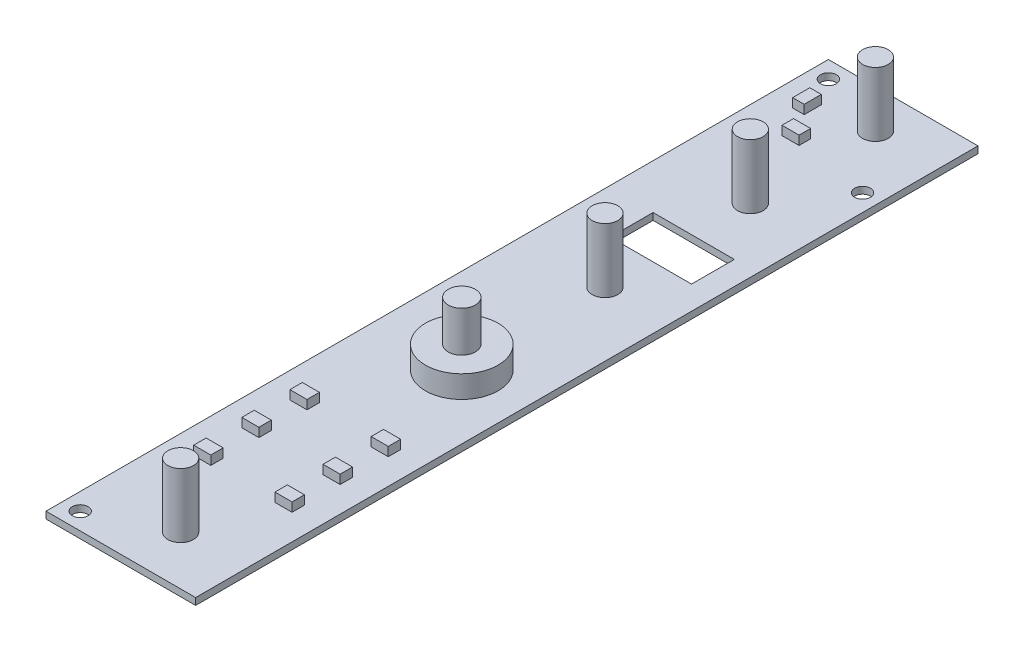
SolidWorks part; units mm, degrees
ref_plane "Front Plane" through (0, 0, 0) normal (0, 0, 1) x (1, 0, 0)
ref_plane "Top Plane" through (0, 0, 0) normal (0, 1, 0) x (1, 0, 0)
ref_plane "Right Plane" through (0, 0, 0) normal (1, 0, 0) x (0, 0, -1)
sketch "pcb" plane through (0, 0, 0) normal (0, 1, 0) x (1, 0, 0)
  line L1 (-17.5, 91.5) -> (17.5, 91.5)
  line L2 (-17.5, 91.5) -> (-17.5, -91.5)
  line L3 (-17.5, -91.5) -> (17.5, -91.5)
  line L4 (17.5, 91.5) -> (17.5, -91.5)
  line L5 (-17.5, 91.5) -> (17.5, -91.5) construction
  line L6 (-17.5, -91.5) -> (17.5, 91.5) construction
  point P0 (0, 0)
  dimension "D1" = 183
  dimension "D2" = 35
extrude "Boss-Extrude1" add sketch "pcb" along normal blind 1.6
sketch "Sketch3" plane through (0, 1.6, 0) normal (0, 1, 0) x (1, 0, 0)
  line L0 (17.5, 91.5) -> (-17.5, 91.5) construction
  line L1 (-17.5, 91.5) -> (-17.5, -91.5) construction
  circle A0 centre (2.5, 82.5) radius 3
  circle A1 centre (2.5, 53.25) radius 3
  circle A2 centre (2.5, 19.25) radius 3
  circle A3 centre (2.5, -80) radius 3
  dimension "D3" = 6
  dimension "D1" = 9
  dimension "D2" = 20
  dimension "D4" = 38.25
  dimension "D5" = 72.25
  dimension "D6" = 171.5
extrude "Boss-Extrude2" add sketch "Sketch3" along normal blind 15
sketch "Sketch4" plane through (0, 1.6, 0) normal (0, 1, 0) x (1, 0, 0)
  line L0 (17.5, 91.5) -> (-17.5, 91.5) construction
  line L1 (-17.5, 91.5) -> (-17.5, -91.5) construction
  circle A0 centre (2.5, -14.25) radius 8.5
  dimension "D3" = 17
  dimension "D1" = 105.75
  dimension "D2" = 20
extrude "Boss-Extrude3" add sketch "Sketch4" along normal blind 5.21
sketch "Sketch5" plane through (0, 6.81, 0) normal (0, 1, 0) x (1, 0, 0)
  circle A0 centre (2.5, -14.25) radius 3.175
  circle A1 centre (2.5, -14.25) radius 8.5 construction
  dimension "D1" = 6.35
extrude "Boss-Extrude4" add sketch "Sketch5" along normal blind 9.52
sketch "Sketch6" plane through (0, 1.6, 0) normal (0, 1, 0) x (1, 0, 0)
  line L0 (-17.5, 91.5) -> (-17.5, -91.5) construction
  line L1 (-11.5, -37.55) -> (-7.5, -37.55)
  line L2 (-11.5, -37.55) -> (-11.5, -40.45)
  line L3 (-11.5, -40.45) -> (-7.5, -40.45)
  line L4 (-7.5, -37.55) -> (-7.5, -40.45)
  line L5 (-11.5, -37.55) -> (-7.5, -40.45) construction
  line L6 (-11.5, -40.45) -> (-7.5, -37.55) construction
  line L7 (17.5, 91.5) -> (-17.5, 91.5) construction
  line L8 (7.5, -37.55) -> (11.5, -37.55)
  line L9 (7.5, -37.55) -> (7.5, -40.45)
  line L10 (7.5, -40.45) -> (11.5, -40.45)
  line L11 (11.5, -37.55) -> (11.5, -40.45)
  line L12 (7.5, -37.55) -> (11.5, -40.45) construction
  line L13 (7.5, -40.45) -> (11.5, -37.55) construction
  line L14 (-11.5, -48.8) -> (-7.5, -48.8)
  line L15 (-11.5, -48.8) -> (-11.5, -51.7)
  line L16 (-11.5, -51.7) -> (-7.5, -51.7)
  line L17 (-7.5, -48.8) -> (-7.5, -51.7)
  line L18 (-11.5, -48.8) -> (-7.5, -51.7) construction
  line L19 (-11.5, -51.7) -> (-7.5, -48.8) construction
  line L26 (7.5, -48.8) -> (11.5, -48.8)
  line L27 (7.5, -48.8) -> (7.5, -51.7)
  line L28 (7.5, -51.7) -> (11.5, -51.7)
  line L29 (11.5, -48.8) -> (11.5, -51.7)
  line L30 (7.5, -48.8) -> (11.5, -51.7) construction
  line L31 (7.5, -51.7) -> (11.5, -48.8) construction
  line L32 (-11.5, -60.05) -> (-7.5, -60.05)
  line L33 (-11.5, -60.05) -> (-11.5, -62.95)
  line L34 (-11.5, -62.95) -> (-7.5, -62.95)
  line L35 (-7.5, -60.05) -> (-7.5, -62.95)
  line L36 (-11.5, -60.05) -> (-7.5, -62.95) construction
  line L37 (-11.5, -62.95) -> (-7.5, -60.05) construction
  line L38 (7.5, -60.05) -> (11.5, -60.05)
  line L39 (7.5, -60.05) -> (7.5, -62.95)
  line L40 (7.5, -62.95) -> (11.5, -62.95)
  line L41 (11.5, -60.05) -> (11.5, -62.95)
  line L42 (7.5, -60.05) -> (11.5, -62.95) construction
  line L43 (7.5, -62.95) -> (11.5, -60.05) construction
  point P0 (-9.5, -39)
  point P12 (9.5, -39)
  point P20 (-9.5, -50.25)
  point P32 (9.5, -50.25)
  point P38 (-9.5, -61.5)
  point P45 (9.5, -61.5)
  dimension "D1" = 8
  dimension "D2" = 130.5
  dimension "D3" = 2.9
  dimension "D4" = 4
  dimension "D5" = 27
  dimension "D6" = 141.75
  dimension "D7" = 153
extrude "Boss-Extrude5" add sketch "Sketch6" along normal blind 2.1
sketch "Sketch7" plane through (0, 1.6, 0) normal (0, 1, 0) x (1, 0, 0)
  line L0 (17.5, 91.5) -> (-17.5, 91.5) construction
  line L1 (17.5, -91.5) -> (17.5, 91.5) construction
  line L2 (-17.5, 91.5) -> (-17.5, -91.5) construction
  circle A0 centre (13.5, 68.5) radius 1.85
  circle A1 centre (-13.5, 87.5) radius 1.85
  circle A2 centre (-13.5, -87.5) radius 1.85
  point P4 (0, 0)
  point P9 (0, 0)
  point P12 (0, 0)
  dimension "D7" = 3.7
  dimension "D1" = 23
  dimension "D2" = 4
  dimension "D3" = 4
  dimension "D4" = 4
  dimension "D5" = 179
extrude "Cut-Extrude2" cut sketch "Sketch7" against normal through all
sketch "Sketch8" plane through (0, 1.6, 0) normal (0, 1, 0) x (1, 0, 0)
  line L0 (-17.5, 91.5) -> (-17.5, -91.5) construction
  line L1 (-7.5, 73.35) -> (-3.5, 73.35)
  line L2 (-7.5, 73.35) -> (-7.5, 70.65)
  line L3 (-7.5, 70.65) -> (-3.5, 70.65)
  line L4 (-3.5, 73.35) -> (-3.5, 70.65)
  line L5 (-7.5, 73.35) -> (-3.5, 70.65) construction
  line L6 (-7.5, 70.65) -> (-3.5, 73.35) construction
  line L7 (17.5, 91.5) -> (-17.5, 91.5) construction
  line L8 (17.5, 91.5) -> (-17.5, 91.5) construction
  line L9 (-11.85, 81.5) -> (-9.15, 81.5)
  line L10 (-11.85, 81.5) -> (-11.85, 77.5)
  line L11 (-11.85, 77.5) -> (-9.15, 77.5)
  line L12 (-9.15, 81.5) -> (-9.15, 77.5)
  line L13 (-11.85, 81.5) -> (-9.15, 77.5) construction
  line L14 (-11.85, 77.5) -> (-9.15, 81.5) construction
  point P0 (-5.5, 72)
  point P5 (-10.5, 79.5)
  point P14 (0, 0)
  point P15 (-10.5, 81.5)
  dimension "D1" = 2.7
  dimension "D2" = 4
  dimension "D3" = 12
  dimension "D4" = 19.5
  dimension "D5" = 7
  dimension "D6" = 10
extrude "Boss-Extrude6" add sketch "Sketch8" along normal blind 2.1
sketch "Sketch9" plane through (0, 1.6, 0) normal (0, 1, 0) x (1, 0, 0)
  line L0 (-17.5, 91.5) -> (-17.5, -91.5) construction
  line L1 (-7, 40) -> (12, 40)
  line L2 (-7, 40) -> (-7, 30)
  line L3 (-7, 30) -> (12, 30)
  line L4 (12, 40) -> (12, 30)
  line L5 (17.5, 91.5) -> (-17.5, 91.5) construction
  dimension "D1" = 10.5
  dimension "D2" = 51.5
  dimension "D3" = 29.5
  dimension "D4" = 61.5
extrude "Cut-Extrude3" cut sketch "Sketch9" against normal through all
